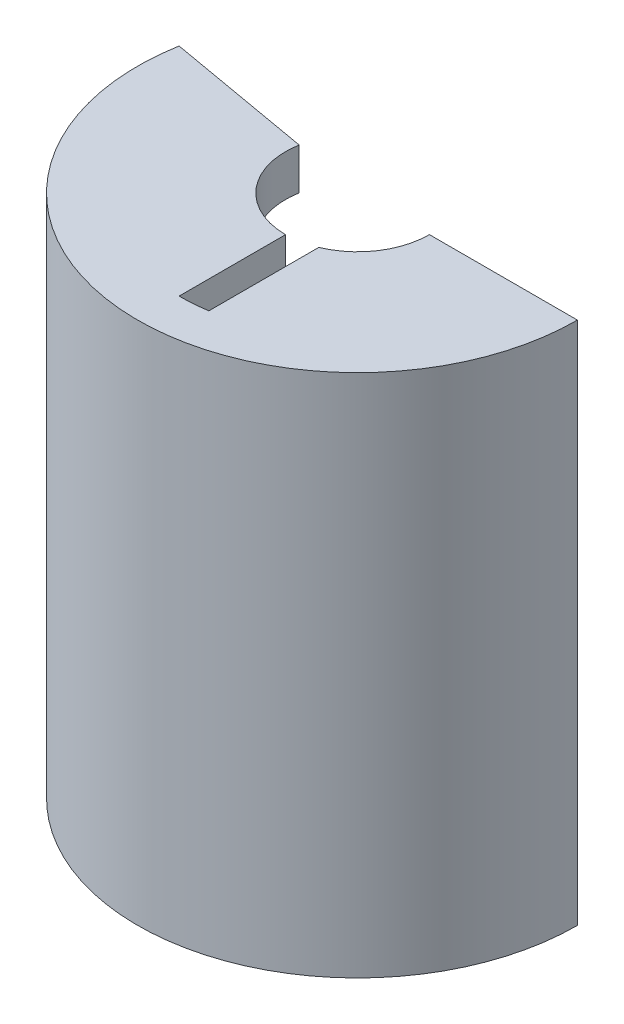
SolidWorks part; units mm, degrees
ref_plane "Front Plane" through (0, 0, 0) normal (0, 0, 1) x (1, 0, 0)
ref_plane "Top Plane" through (0, 0, 0) normal (0, 1, 0) x (1, 0, 0)
ref_plane "Right Plane" through (0, 0, 0) normal (1, 0, 0) x (0, 0, -1)
sketch "Sketch1" plane through (0, 0, 0) normal (0, 0, 1) x (1, 0, 0)
  line L0 (5.2, 99.643) -> (12.8971, 99.643)
  line L1 (12.8971, 99.643) -> (12.8971, 77.4)
  line L2 (12.8971, 77.4) -> (9.725, 77.4)
  line L3 (9.725, 77.4) -> (9.725, 67.748)
  line L4 (9.725, 67.748) -> (2.7, 67.748)
  line L5 (2.7, 67.748) -> (2.7, 64.748)
  line L6 (2.7, 64.748) -> (15.8971, 64.748)
  line L7 (15.8971, 64.748) -> (15.8971, 102.643)
  line L8 (15.8971, 102.643) -> (5.2, 102.643)
  line L9 (5.2, 102.643) -> (5.2, 99.643)
  line L10 (12.1887, 99.543) -> (-12.1584, 99.543) construction
  line L11 (-9.1223, 67.848) -> (9.1425, 67.848) construction
  line L12 (6.6833, 77.5) -> (11.6955, 77.5) construction
  line L13 (9.525, 68.229) -> (9.525, 77.119) construction
  line L14 (12.6971, 91.5674) -> (12.6971, 99.035) construction
  line L15 (5, 86.6812) -> (5, 346.6812) construction
  line L17 (2.5, 55) -> (2.5, 77.2) construction
  dimension "D1" = 0.1
  dimension "D2" = 0.1
  dimension "D3" = 0.1
  dimension "D4" = 0.2
  dimension "D5" = 0.2
  dimension "D6" = 3
  dimension "D7" = 3
  dimension "D8" = 3
  dimension "D9" = 0.2
  dimension "D10" = 0.2
ref_axis "Axis1" through (0, 104.5377, 0) along (0, -1, 0)
revolve "Revolve1" add sketch "Sketch1" angle 190 about axis through (0, 104.5377, 0) along (0, -1, 0)
sketch "Sketch2" plane through (0, 102.643, 0) normal (0, 1, 0) x (1, 0, 0)
  line L0 (0, 0) -> (0, -12.8971)
  line L1 (0, 0) -> (1.9992, 0)
  line L2 (1.9992, 0) -> (1.9992, -12.7412)
  arc A0 (-12.7012, 2.2396) -> (12.8971, 0) centre (0, 0) ccw construction
  arc A1 (0, -12.8971) -> (1.9992, -12.7412) centre (0, 0) ccw
extrude "Cut-Extrude1" cut sketch "Sketch2" against normal through all
